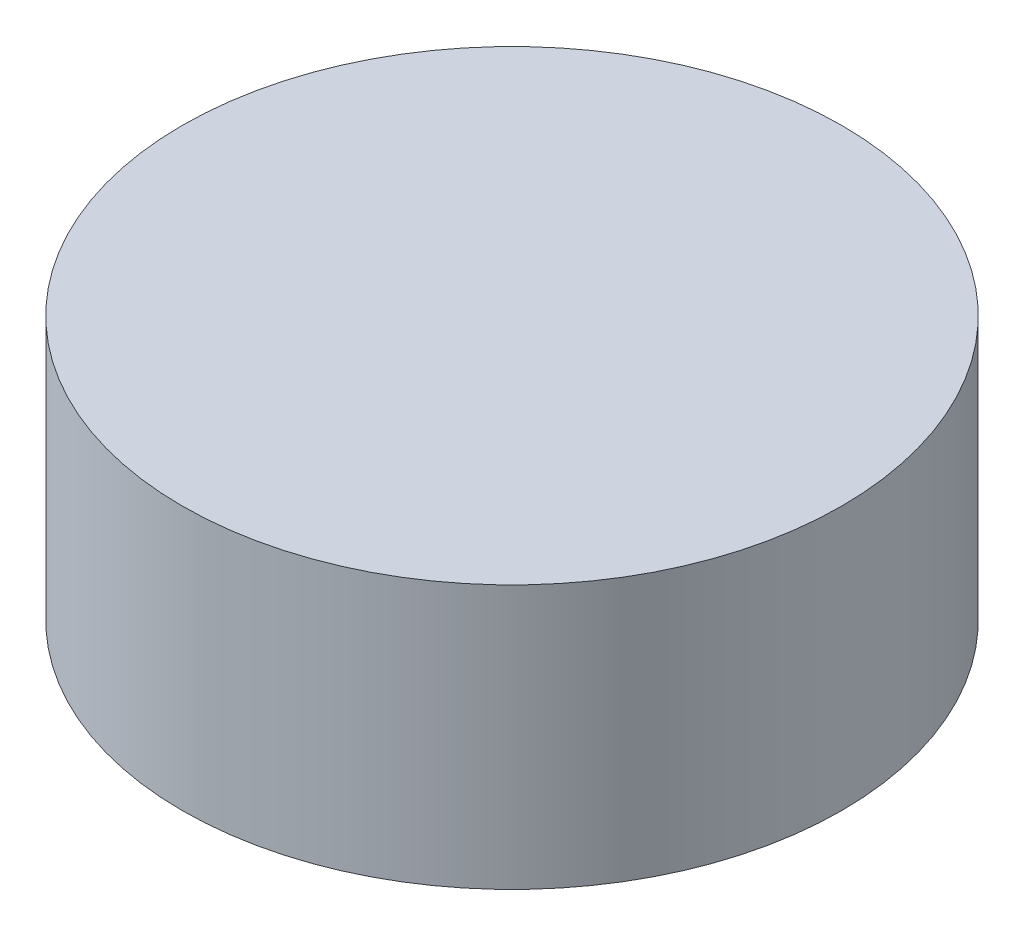
SolidWorks part; units mm, degrees
ref_plane "Front Plane" through (0, 0, 0) normal (0, 0, 1) x (1, 0, 0)
ref_plane "Top Plane" through (0, 0, 0) normal (0, 1, 0) x (1, 0, 0)
ref_plane "Right Plane" through (0, 0, 0) normal (1, 0, 0) x (0, 0, -1)
sketch "Sketch1" plane through (0, 0, 0) normal (0, 1, 0) x (1, 0, 0)
  circle A0 centre (0, 0) radius 3.9688
  dimension "D1" = 7.9375
extrude "Boss-Extrude1" add sketch "Sketch1" along normal blind 3.175
